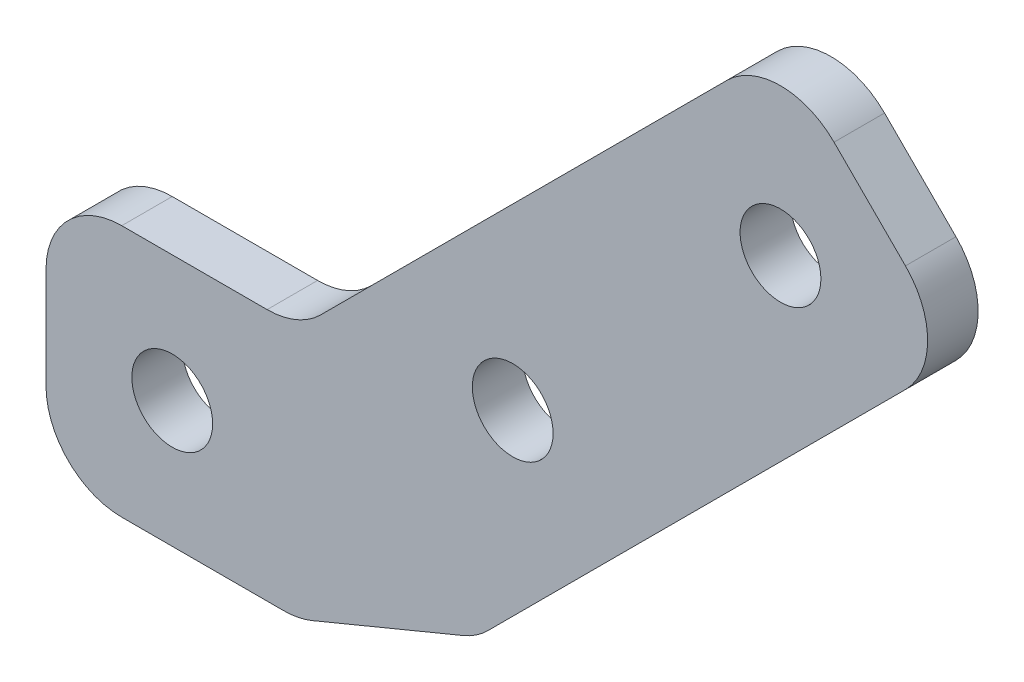
SolidWorks part; units mm, degrees
material "1060 合金"
ref_plane "正面" through (0, 0, 0) normal (0, 0, 1) x (1, 0, 0)
ref_plane "平面" through (0, 0, 0) normal (0, 1, 0) x (1, 0, 0)
ref_plane "右側面" through (0, 0, 0) normal (1, 0, 0) x (0, 0, -1)
sketch "ｽｹｯﾁ1" plane through (0, 0, 0) normal (0, 0, 1) x (1, 0, 0)
  line L0 (10, 10) -> (29.0919, 29.0919)
  line L1 (0, 0) -> (10, 0)
  line L2 (0, 0) -> (0, 10)
  line L3 (0, 10) -> (10, 10)
  line L4 (10, 0) -> (10, 10)
  line L5 (10, 10) -> (17.0711, 2.9289)
  line L6 (29.0919, 29.0919) -> (36.163, 22.0208)
  line L7 (17.0711, 2.9289) -> (36.163, 22.0208)
  line L8 (0, 5) -> (10, 5) construction
  line L9 (32.6274, 25.5563) -> (13.5355, 6.4645) construction
  line L10 (10, 0) -> (17.0711, 2.9289)
  circle A1 centre (5, 5) radius 1.6
  circle A2 centre (29.0919, 22.0208) radius 1.6
  circle A3 centre (18.4853, 11.4142) radius 1.6
  dimension "D3" = 5
  dimension "D4" = 5
  dimension "D5" = 3.2
  dimension "D10" = 3.2
  dimension "D11" = 5
  dimension "D12" = 7
  dimension "D13" = 3.2
  dimension "D1" = 10
  dimension "D2" = 10
  dimension "D8" = 45
  dimension "D9" = 27
extrude "ﾎﾞｽ - 押し出し2" add sketch "ｽｹｯﾁ1" along normal blind 2
fillet "ﾌｨﾚｯﾄ1" radius 3 7 edges at (0, 0, 1) (0, 10, 1) (10, 0, 1) (17.0711, 2.9289, 1) (36.163, 22.0208, 1) (29.0919, 29.0919, 1) (10, 10, 1)
